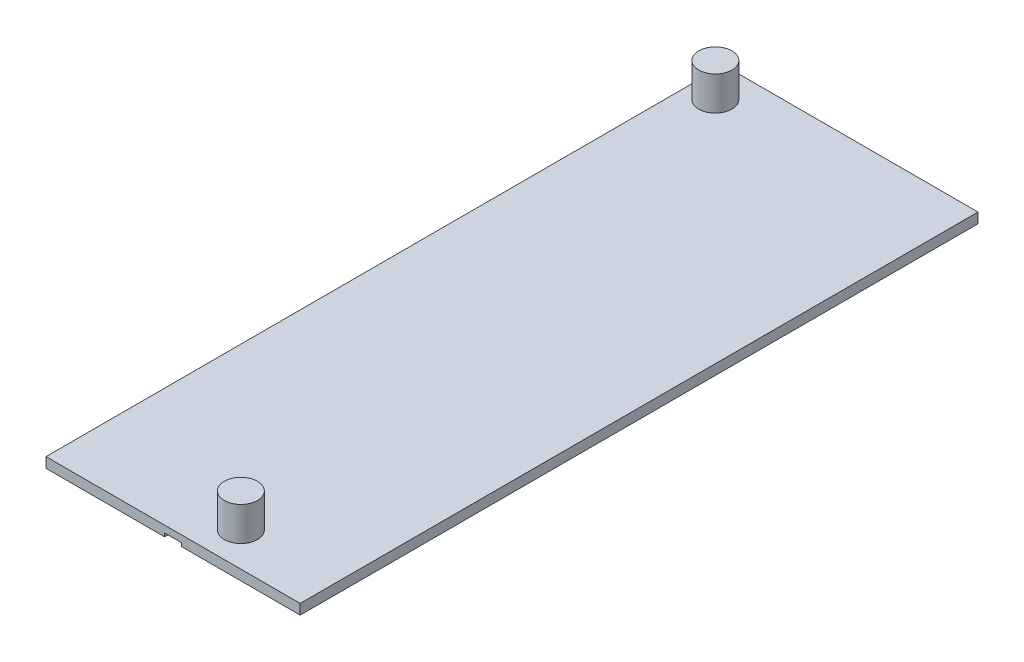
SolidWorks part; units mm, degrees
ref_plane "Front Plane" through (0, 0, 0) normal (0, 0, 1) x (1, 0, 0)
ref_plane "Top Plane" through (0, 0, 0) normal (0, 1, 0) x (1, 0, 0)
ref_plane "Right Plane" through (0, 0, 0) normal (1, 0, 0) x (0, 0, -1)
sketch "Sketch1" plane through (0, 0, 0) normal (0, 0, 1) x (1, 0, 0)
  line L1 (0, 0) -> (75, 0)
  line L2 (0, 0) -> (0, 3)
  line L3 (0, 3) -> (75, 3)
  line L4 (75, 0) -> (75, 3)
  dimension "D1" = 3
  dimension "D2" = 75
extrude "Boss-Extrude1" add sketch "Sketch1" along normal blind 200
sketch "Sketch2" plane through (0, 3, 0) normal (0, 1, 0) x (1, 0, 0)
  line L1 (150, 0) -> (-75, 0)
  line L2 (150, 0) -> (150, -200)
  line L3 (150, -200) -> (-75, -200)
  line L4 (-75, 0) -> (-75, -200)
  line L5 (137.5, -200) -> (-62.5, -200)
  line L6 (137.5, -200) -> (137.5, 0)
  line L7 (137.5, 0) -> (-62.5, 0)
  line L8 (-62.5, -200) -> (-62.5, 0)
  line L9 (75, -200) -> (0, -200) construction
  line L10 (75, 0) -> (0, 0) construction
  line L11 (75, -200) -> (75, 0) construction
  circle A0 centre (127.5, -190) radius 4.9
  circle A1 centre (87.5, -10) radius 4.9
  circle A2 centre (47.5, -190) radius 4.9
  circle A3 centre (7.5, -10) radius 4.9
  dimension "D4" = 10
  dimension "D5" = 10
  dimension "D6" = 9.8
  dimension "D7" = 9.8
  dimension "D8" = 10
  dimension "D9" = 40
  dimension "D11" = 10
  dimension "D12" = 10
  dimension "D13" = 80
  dimension "D14" = 80
  dimension "D15" = 9.8
  dimension "D16" = 9.8
  dimension "D1" = 225
  dimension "D2" = 12.5
  dimension "D3" = 12.5
  dimension "D10" = 75
extrude "Boss-Extrude2" add sketch "Sketch2" along normal blind 10 contours A3 | A2
sketch "Sketch3" plane through (0, 0, 0) normal (0, -1, 0) x (1, 0, 0)
  line L0 (0, 200) -> (75, 200) construction
  line L1 (35, 200) -> (40, 200)
  line L2 (35, 200) -> (35, 0)
  line L3 (35, 0) -> (40, 0)
  line L4 (40, 200) -> (40, 0)
  line L5 (0, 0) -> (75, 0) construction
  point P8 (37.5, 200)
  point P9 (37.5, 200)
  dimension "D1" = 5
extrude "Cut-Extrude1" cut sketch "Sketch3" against normal blind 1
